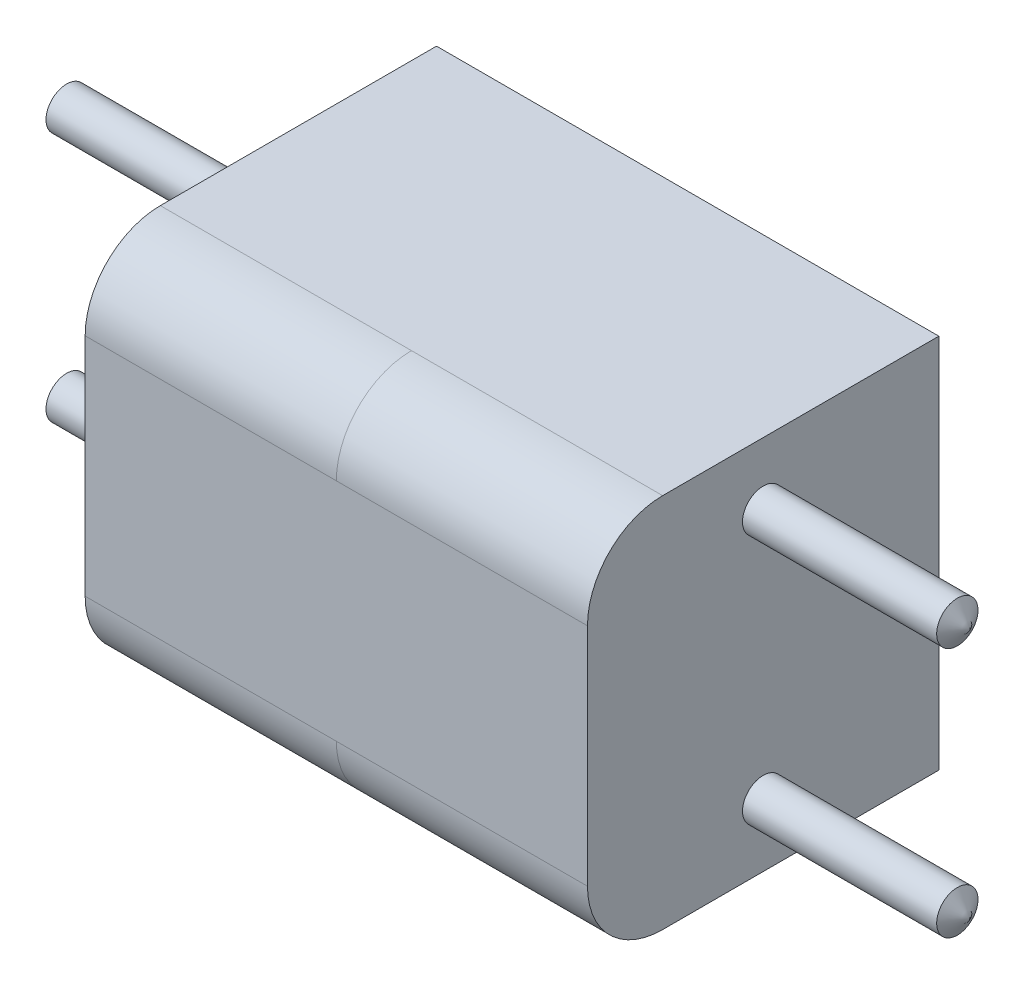
SolidWorks part; units mm, degrees
material "Abzugskörper"
ref_plane "Ebene vorne" through (0, 0, 0) normal (0, 0, 1) x (1, 0, 0)
ref_plane "Ebene oben" through (0, 0, 0) normal (0, 1, 0) x (1, 0, 0)
ref_plane "Ebene rechts" through (0, 0, 0) normal (1, 0, 0) x (0, 0, -1)
sketch "Skizze1" plane through (0, 0, 0) normal (1, 0, 0) x (0, 0, -1)
  line L1 (0, 15.0022) -> (-28.05, 15.0022)
  line L2 (0, 15.0022) -> (0, -15.0022)
  line L3 (0, -15.0022) -> (-28.05, -15.0023)
  line L4 (-28.05, 15.0022) -> (-28.05, -15.0023)
  point P4 (-28.05, 0)
  dimension "#b1" = 28.05
  dimension "#l1" = 30.0045
extrude "Aufsatz-Linear austragen1" add sketch "Skizze1" along normal blind 20.05
fillet "Verrundung1" radius 6 2 edges at (10.025, -15.0023, 28.05) (10.025, 15.0022, 28.05)
sketch "Skizze2" plane through (20.05, 0, 0) normal (1, 0, 0) x (0, 0, -1)
  line L0 (-28.05, 0) -> (0, 0) construction
  line L1 (-28.05, 9.0022) -> (-28.05, -9.0023) construction
  line L2 (-14.025, 0) -> (-14.025, 10) construction
  line L4 (-14.025, 0) -> (-14.025, -10) construction
  circle A0 centre (-14.025, 10) radius 1.65
  circle A1 centre (-14.025, -10) radius 1.65
  dimension "d4" = 3.3
  dimension "a1" = 20
extrude "Aufsatz-Linear austragen2" add sketch "Skizze2" along normal blind 15.5
ref_plane "Ebene1" through (0, 0, 14.025) normal (0, 0, 1) x (1, 0, 0)
sketch "Skizze3" plane through (0, 0, 14.025) normal (0, 0, 1) x (1, 0, 0)
  line L0 (35.55, 8.35) -> (35.55, 11.65) construction
  line L1 (35.55, 8.35) -> (35.55, 11.65) construction
  line L2 (35.55, 10) -> (36.5414, 10)
  line L3 (36.5414, 10) -> (35.55, 11.65)
  line L4 (35.55, 11.65) -> (35.55, 10)
  line L5 (36.5414, 10) -> (35.55, 8.35) construction
  dimension "D1" = 118
revolve "Rotation1" add sketch "Skizze3" angle 360 about axis through (35.55, 10, 14.025) along (-1, 0, 0)
sketch "Skizze4" plane through (0, 0, 14.025) normal (0, 0, 1) x (1, 0, 0)
  line L0 (35.55, -11.65) -> (35.55, -8.35) construction
  line L1 (35.55, -11.65) -> (35.55, -8.35) construction
  line L2 (35.55, -10) -> (36.5414, -10)
  line L3 (36.5414, -10) -> (35.55, -8.35)
  line L4 (35.55, -8.35) -> (35.55, -10)
  line L5 (36.5414, -10) -> (35.55, -11.65) construction
  dimension "D1" = 118
revolve "Rotation2" add sketch "Skizze4" angle 360 about axis through (35.55, -10, 14.025) along (-1, 0, 0)
mirror "Spiegeln1" about plane through (0, 0, 0) normal (-1, 0, 0) of "Verrundung1", "Aufsatz-Linear austragen1", "Aufsatz-Linear austragen2", "Rotation1", "Rotation2"
